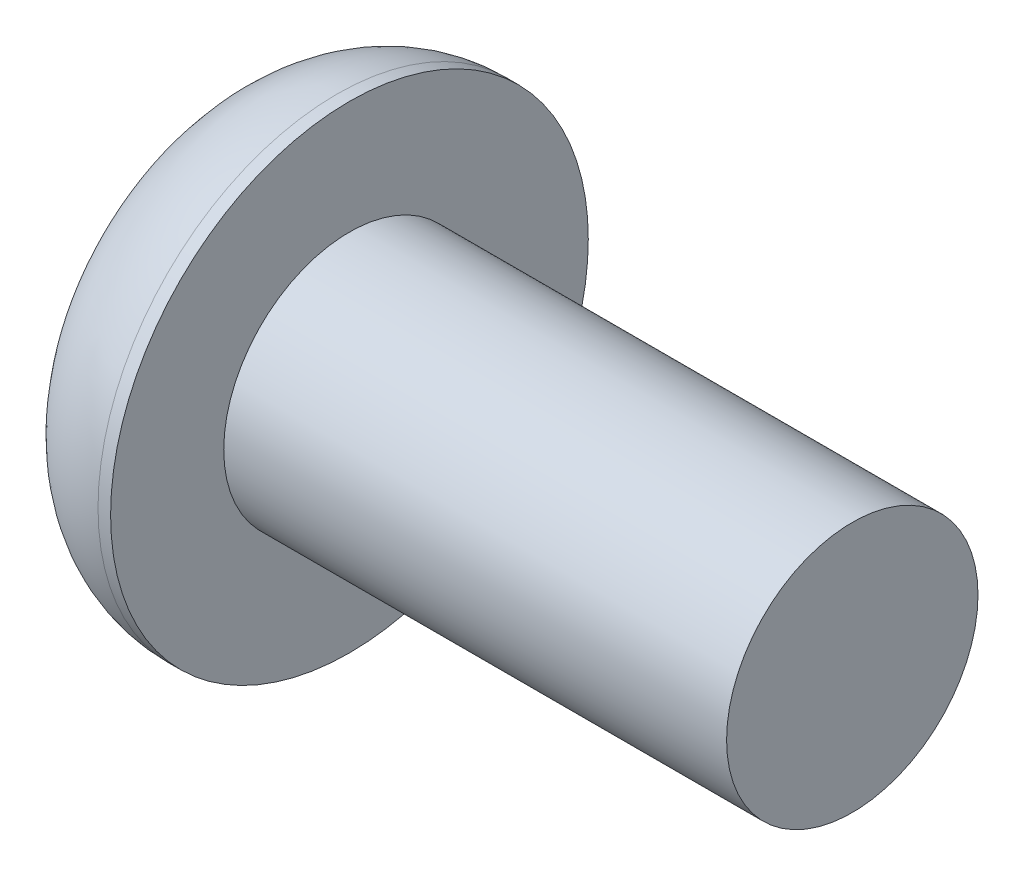
SolidWorks part; units mm, degrees
material "AISI 1020"
ref_plane "Front Plane" through (0, 0, 0) normal (0, 0, 1) x (1, 0, 0)
ref_plane "Top Plane" through (0, 0, 0) normal (0, 1, 0) x (1, 0, 0)
ref_plane "Right Plane" through (0, 0, 0) normal (1, 0, 0) x (0, 0, -1)
sketch "Sketch1" plane through (0, 0, 0) normal (0, 1, 0) x (1, 0, 0)
  line L0 (0, 0) -> (12.75, 0)
  line L1 (12.75, 0) -> (12.75, 2.5)
  line L2 (12.75, 2.5) -> (2.75, 2.5)
  line L3 (2.75, 2.5) -> (2.75, 4.75)
  line L4 (2.75, 4.75) -> (2.5, 4.75)
  line L5 (0, 2.25) -> (0, 0)
  line L6 (0, 0) -> (-8.9321, 0) construction
  arc A0 (0, 2.25) -> (2.5, 4.75) centre (2.5, 2.25) cw
  point P11 (0, 4.75)
  dimension "D5" = 2.5
  dimension "D1" = 2.5
  dimension "D2" = 10
  dimension "D3" = 2.75
  dimension "D4" = 4.75
revolve "Revolve1" add sketch "Sketch1" angle 360 about L6
sketch "Sketch2" plane through (0, 0, 0) normal (-1, 0, 0) x (0, 0, 1)
  line L1 (1.7321, 0) -> (0.866, 1.5)
  line L2 (0.866, 1.5) -> (-0.866, 1.5)
  line L3 (-0.866, 1.5) -> (-1.7321, 0)
  line L4 (-1.7321, 0) -> (-0.866, -1.5)
  line L5 (-0.866, -1.5) -> (0.866, -1.5)
  line L6 (0.866, -1.5) -> (1.7321, 0)
  circle A0 centre (0, 0) radius 1.5 construction
  dimension "D1" = 3
extrude "Cut-Extrude1" cut sketch "Sketch2" against normal blind 1.56
